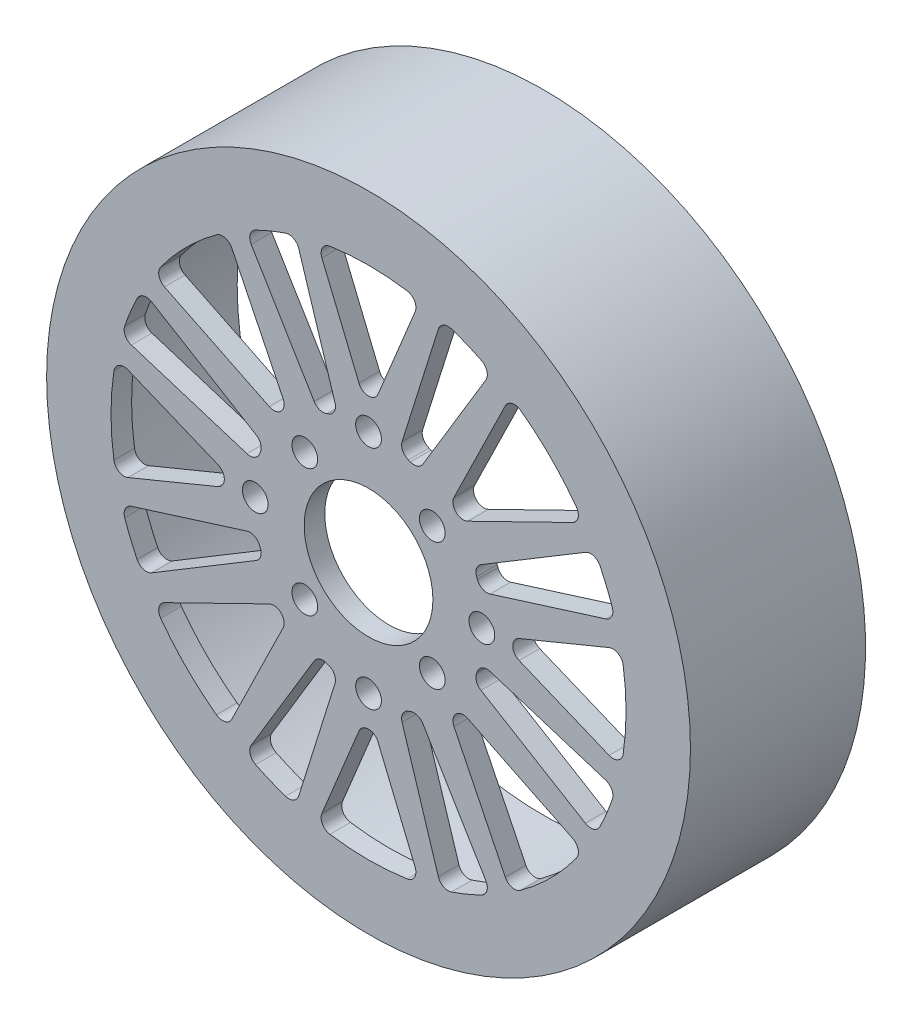
SolidWorks part; units mm, degrees
ref_plane "前视基准面" through (0, 0, 0) normal (0, 0, 1) x (1, 0, 0)
ref_plane "上视基准面" through (0, 0, 0) normal (0, 1, 0) x (1, 0, 0)
ref_plane "右视基准面" through (0, 0, 0) normal (1, 0, 0) x (0, 0, -1)
sketch "草图1" plane through (0, 0, 0) normal (0, 0, 1) x (1, 0, 0)
  line L0 (0, 0) -> (0, 22) construction
  line L1 (0, 0) -> (12.3744, 12.3744) construction
  circle A0 centre (0, 0) radius 72.5
  circle A1 centre (0, 0) radius 17.5 construction
  circle A2 centre (0, 0) radius 22 construction
  circle A3 centre (0, 22) radius 2.5
  circle A4 centre (12.3744, 12.3744) radius 2.5
  circle A5 centre (22, 0) radius 2.5
  circle A6 centre (12.3744, -12.3744) radius 2.5
  circle A7 centre (0, -22) radius 2.5
  circle A8 centre (-12.3744, -12.3744) radius 2.5
  circle A9 centre (-22, 0) radius 2.5
  circle A10 centre (-12.3744, 12.3744) radius 2.5
  point P24 (0, 0)
  dimension "D1" = 145
  dimension "D2" = 35
  dimension "D3" = 44
  dimension "D4" = 5
  dimension "D6" = 4
  dimension "D5" = 45
extrude "凸台-拉伸1" add sketch "草图1" along normal mid plane 4
sketch "草图2" plane through (0, 0, 2) normal (0, 0, 1) x (1, 0, 0)
  circle A0 centre (0, 0) radius 12.5
  dimension "D1" = 25
extrude "切除-拉伸1" cut sketch "草图2" against normal blind 4
sketch "草图3" plane through (0, 0, -2) normal (0, 0, -1) x (-1, 0, 0)
  circle A0 centre (0, 0) radius 72.5 construction
  circle A1 centre (0, 0) radius 72.5
  circle A2 centre (0, 0) radius 59.5
  dimension "D1" = 13
extrude "凸台-拉伸2" add sketch "草图3" along normal blind 30
sketch "草图4" plane through (0, 0, -32) normal (0, 0, -1) x (-1, 0, 0)
  circle A0 centre (0, 0) radius 72.5 construction
  circle A1 centre (0, 0) radius 72.5
  circle A2 centre (0, 0) radius 62.5
  dimension "D1" = 10
extrude "切除-拉伸2" cut sketch "草图4" against normal blind 44
sketch "草图5" plane through (0, 0, -2) normal (0, 0, -1) x (-1, 0, 0)
  line L0 (-9.0524, 46.6935) -> (-1.8488, 29.2371)
  line L1 (0, 0) -> (0, 30) construction
  line L2 (9.0524, 46.6935) -> (1.8488, 29.2371)
  line L3 (-13.5532, 46.0406) -> (-6.5123, 23.6064)
  line L4 (13.5532, 46.0406) -> (6.5123, 23.6064)
  line L5 (46.6935, 9.0524) -> (29.2371, 1.8488)
  line L6 (46.6935, -9.0524) -> (29.2371, -1.8488)
  line L7 (46.0406, -13.5532) -> (23.6064, -6.5123)
  line L8 (46.0406, 13.5532) -> (23.6064, 6.5123)
  line L9 (9.0524, -46.6935) -> (1.8488, -29.2371)
  line L10 (-9.0524, -46.6935) -> (-1.8488, -29.2371)
  line L11 (-13.5532, -46.0406) -> (-6.5123, -23.6064)
  line L12 (13.5532, -46.0406) -> (6.5123, -23.6064)
  line L13 (-46.6935, -9.0524) -> (-29.2371, -1.8488)
  line L14 (-46.6935, 9.0524) -> (-29.2371, 1.8488)
  line L15 (-46.0406, 13.5532) -> (-23.6064, 6.5123)
  line L16 (-46.0406, -13.5532) -> (-23.6064, -6.5123)
  line L17 (-16.5882, 19.2636) -> (-26.5456, 39.6181)
  line L18 (0, 0) -> (-12.3744, 12.3744) construction
  line L19 (-19.2636, 16.5882) -> (-39.6181, 26.5456)
  line L20 (-41.7121, 27.5699) -> (-27.5699, 41.7121) construction
  line L21 (-10, 48.9898) -> (10, 48.9898) construction
  line L22 (-22.7777, 42.0989) -> (-10.5577, 21.8157)
  line L23 (-42.0989, 22.7777) -> (-21.8157, 10.5577)
  line L24 (42.0989, 22.7777) -> (21.8157, 10.5577)
  line L25 (19.2636, 16.5882) -> (39.6181, 26.5456)
  line L26 (16.5882, 19.2636) -> (26.5456, 39.6181)
  line L27 (22.7777, 42.0989) -> (10.5577, 21.8157)
  line L28 (22.7777, -42.0989) -> (10.5577, -21.8157)
  line L29 (16.5882, -19.2636) -> (26.5456, -39.6181)
  line L30 (19.2636, -16.5882) -> (39.6181, -26.5456)
  line L31 (42.0989, -22.7777) -> (21.8157, -10.5577)
  line L32 (-42.0989, -22.7777) -> (-21.8157, -10.5577)
  line L33 (-19.2636, -16.5882) -> (-39.6181, -26.5456)
  line L34 (-16.5882, -19.2636) -> (-26.5456, -39.6181)
  line L35 (-22.7777, -42.0989) -> (-10.5577, -21.8157)
  circle A0 centre (0, 0) radius 30 construction
  arc A1 (-29.523, 40.3533) -> (-40.3533, 29.523) centre (0, 0) ccw
  arc A2 (-1.8488, 29.2371) -> (1.8488, 29.2371) centre (0, 30) ccw
  arc A3 (-21.1293, -7.7332) -> (-20.9827, -8.1226) centre (0, 0) ccw
  arc A4 (29.2371, 1.8488) -> (29.2371, -1.8488) centre (30, 0) ccw
  arc A5 (1.8488, -29.2371) -> (-1.8488, -29.2371) centre (0, -30) ccw
  arc A6 (-29.2371, -1.8488) -> (-29.2371, 1.8488) centre (-30, 0) ccw
  arc A7 (-16.5882, 19.2636) -> (-19.2636, 16.5882) centre (-18.3848, 18.3848) cw
  arc A8 (19.2636, 16.5882) -> (16.5882, 19.2636) centre (18.3848, 18.3848) cw
  arc A9 (16.5882, -19.2636) -> (19.2636, -16.5882) centre (18.3848, -18.3848) cw
  arc A10 (-19.2636, -16.5882) -> (-16.5882, -19.2636) centre (-18.3848, -18.3848) cw
  arc A11 (-16.1056, 47.3351) -> (-21.9423, 44.9281) centre (0, 0) ccw
  arc A12 (7.5038, 49.4337) -> (-7.5038, 49.4337) centre (0, 0) ccw
  arc A13 (21.9423, 44.9281) -> (16.1056, 47.3351) centre (0, 0) ccw
  arc A14 (40.3533, 29.523) -> (29.523, 40.3533) centre (0, 0) ccw
  arc A15 (47.3351, 16.1056) -> (44.9281, 21.9423) centre (0, 0) ccw
  arc A16 (49.4337, -7.5038) -> (49.4337, 7.5038) centre (0, 0) ccw
  arc A17 (44.9281, -21.9423) -> (47.3351, -16.1056) centre (0, 0) ccw
  arc A18 (29.523, -40.3533) -> (40.3533, -29.523) centre (0, 0) ccw
  arc A19 (16.1056, -47.3351) -> (21.9423, -44.9281) centre (0, 0) ccw
  arc A20 (-7.5038, -49.4337) -> (7.5038, -49.4337) centre (0, 0) ccw
  arc A21 (-21.9423, -44.9281) -> (-16.1056, -47.3351) centre (0, 0) ccw
  arc A22 (-40.3533, -29.523) -> (-29.523, -40.3533) centre (0, 0) ccw
  arc A23 (-47.3351, -16.1056) -> (-44.9281, -21.9423) centre (0, 0) ccw
  arc A24 (-44.9281, 21.9423) -> (-47.3351, 16.1056) centre (0, 0) ccw
  arc A25 (-49.4337, 7.5038) -> (-49.4337, -7.5038) centre (0, 0) ccw
  arc A26 (-8.1226, -20.9827) -> (-7.7332, -21.1293) centre (0, 0) ccw
  arc A27 (-20.9827, 8.1226) -> (-21.1293, 7.7332) centre (0, 0) ccw
  arc A28 (-7.7332, 21.1293) -> (-8.1226, 20.9827) centre (0, 0) ccw
  arc A29 (8.1226, 20.9827) -> (7.7332, 21.1293) centre (0, 0) ccw
  arc A30 (21.1293, 7.7332) -> (20.9827, 8.1226) centre (0, 0) ccw
  arc A31 (20.9827, -8.1226) -> (21.1293, -7.7332) centre (0, 0) ccw
  arc A32 (7.7332, -21.1293) -> (8.1226, -20.9827) centre (0, 0) ccw
  arc A33 (6.5123, 23.6064) -> (7.7332, 21.1293) centre (8.4206, 23.0075) ccw
  arc A34 (10.5577, 21.8157) -> (8.1226, 20.9827) centre (8.8446, 22.8478) cw
  arc A35 (21.8157, 10.5577) -> (20.9827, 8.1226) centre (22.8478, 8.8446) ccw
  arc A36 (23.6064, 6.5123) -> (21.1293, 7.7332) centre (23.0075, 8.4206) cw
  arc A37 (23.6064, -6.5123) -> (21.1293, -7.7332) centre (23.0075, -8.4206) ccw
  arc A38 (21.8157, -10.5577) -> (20.9827, -8.1226) centre (22.8478, -8.8446) cw
  arc A39 (10.5577, -21.8157) -> (8.1226, -20.9827) centre (8.8446, -22.8478) ccw
  arc A40 (6.5123, -23.6064) -> (7.7332, -21.1293) centre (8.4206, -23.0075) cw
  arc A41 (-6.5123, -23.6064) -> (-7.7332, -21.1293) centre (-8.4206, -23.0075) ccw
  arc A42 (-10.5577, -21.8157) -> (-8.1226, -20.9827) centre (-8.8446, -22.8478) cw
  arc A43 (-21.8157, -10.5577) -> (-20.9827, -8.1226) centre (-22.8478, -8.8446) ccw
  arc A44 (-23.6064, -6.5123) -> (-21.1293, -7.7332) centre (-23.0075, -8.4206) cw
  arc A45 (-23.6064, 6.5123) -> (-21.1293, 7.7332) centre (-23.0075, 8.4206) ccw
  arc A46 (-21.8157, 10.5577) -> (-20.9827, 8.1226) centre (-22.8478, 8.8446) cw
  arc A47 (-42.0989, 22.7777) -> (-44.9281, 21.9423) centre (-43.131, 21.0646) ccw
  arc A48 (-46.0406, 13.5532) -> (-47.3351, 16.1056) centre (-45.4417, 15.4614) cw
  arc A49 (-46.6935, 9.0524) -> (-49.4337, 7.5038) centre (-47.4564, 7.2036) ccw
  arc A50 (-46.6935, -9.0524) -> (-49.4337, -7.5038) centre (-47.4564, -7.2036) cw
  arc A51 (-46.0406, -13.5532) -> (-47.3351, -16.1056) centre (-45.4417, -15.4614) ccw
  arc A52 (-42.0989, -22.7777) -> (-44.9281, -21.9423) centre (-43.131, -21.0646) cw
  arc A53 (-39.6181, -26.5456) -> (-40.3533, -29.523) centre (-38.7392, -28.3421) ccw
  arc A54 (-26.5456, -39.6181) -> (-29.523, -40.3533) centre (-28.3421, -38.7392) cw
  arc A55 (-22.7777, -42.0989) -> (-21.9423, -44.9281) centre (-21.0646, -43.131) ccw
  arc A56 (-13.5532, -46.0406) -> (-16.1056, -47.3351) centre (-15.4614, -45.4417) cw
  arc A57 (-9.0524, -46.6935) -> (-7.5038, -49.4337) centre (-7.2036, -47.4564) ccw
  arc A58 (9.0524, -46.6935) -> (7.5038, -49.4337) centre (7.2036, -47.4564) cw
  arc A59 (13.5532, -46.0406) -> (16.1056, -47.3351) centre (15.4614, -45.4417) ccw
  arc A60 (22.7777, -42.0989) -> (21.9423, -44.9281) centre (21.0646, -43.131) cw
  arc A61 (26.5456, -39.6181) -> (29.523, -40.3533) centre (28.3421, -38.7392) ccw
  arc A62 (39.6181, -26.5456) -> (40.3533, -29.523) centre (38.7392, -28.3421) cw
  arc A63 (42.0989, -22.7777) -> (44.9281, -21.9423) centre (43.131, -21.0646) ccw
  arc A64 (46.0406, -13.5532) -> (47.3351, -16.1056) centre (45.4417, -15.4614) cw
  arc A65 (46.6935, -9.0524) -> (49.4337, -7.5038) centre (47.4564, -7.2036) ccw
  arc A66 (46.6935, 9.0524) -> (49.4337, 7.5038) centre (47.4564, 7.2036) cw
  arc A67 (46.0406, 13.5532) -> (47.3351, 16.1056) centre (45.4417, 15.4614) ccw
  arc A68 (42.0989, 22.7777) -> (44.9281, 21.9423) centre (43.131, 21.0646) cw
  arc A69 (39.6181, 26.5456) -> (40.3533, 29.523) centre (38.7392, 28.3421) ccw
  arc A70 (26.5456, 39.6181) -> (29.523, 40.3533) centre (28.3421, 38.7392) cw
  arc A71 (22.7777, 42.0989) -> (21.9423, 44.9281) centre (21.0646, 43.131) ccw
  arc A72 (13.5532, 46.0406) -> (16.1056, 47.3351) centre (15.4614, 45.4417) cw
  arc A73 (9.0524, 46.6935) -> (7.5038, 49.4337) centre (7.2036, 47.4564) ccw
  arc A74 (-9.0524, 46.6935) -> (-7.5038, 49.4337) centre (-7.2036, 47.4564) cw
  arc A75 (-39.6181, 26.5456) -> (-40.3533, 29.523) centre (-38.7392, 28.3421) cw
  arc A76 (-26.5456, 39.6181) -> (-29.523, 40.3533) centre (-28.3421, 38.7392) ccw
  arc A77 (-13.5532, 46.0406) -> (-16.1056, 47.3351) centre (-15.4614, 45.4417) ccw
  arc A78 (-22.7777, 42.0989) -> (-21.9423, 44.9281) centre (-21.0646, 43.131) cw
  arc A79 (-10.5577, 21.8157) -> (-8.1226, 20.9827) centre (-8.8446, 22.8478) ccw
  arc A80 (-6.5123, 23.6064) -> (-7.7332, 21.1293) centre (-8.4206, 23.0075) cw
  circle A81 centre (0, 0) radius 26 construction
  dimension "D1" = 2
  dimension "D4" = 45
  dimension "D5" = 2
  dimension "D7" = 50
  dimension "D8" = 2
  dimension "D2" = 30
  dimension "D3" = 20
  dimension "D6" = 26
  dimension "D9" = 5
  dimension "D10" = 5
  dimension "D11" = 8.5
  dimension "D12" = 8.5
extrude "切除-拉伸3" cut sketch "草图5" against normal blind 44
